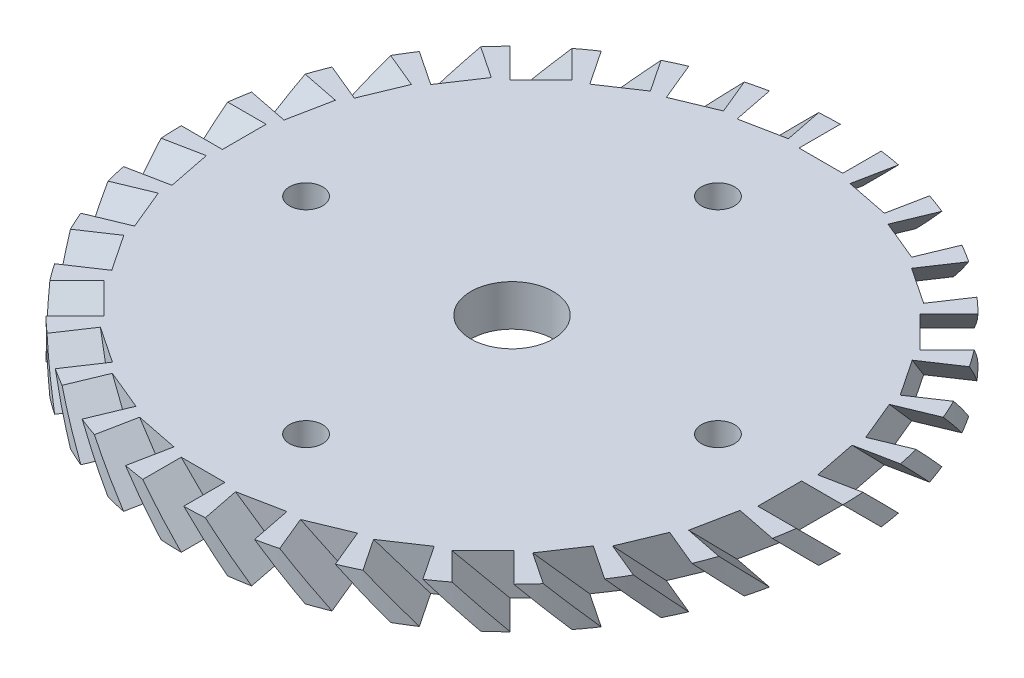
SolidWorks part; units mm, degrees
material "Nickel"
ref_plane "Front Plane" through (0, 0, 0) normal (0, 0, 1) x (1, 0, 0)
ref_plane "Top Plane" through (0, 0, 0) normal (0, 1, 0) x (1, 0, 0)
ref_plane "Right Plane" through (0, 0, 0) normal (1, 0, 0) x (0, 0, -1)
sketch "Sketch1" plane through (0, 0, 0) normal (0, 1, 0) x (1, 0, 0)
  circle A0 centre (0, 0) radius 6.35
  circle A1 centre (0, 0) radius 50.8
  dimension "D1" = 12.7
  dimension "D2" = 101.6
extrude "Boss-Extrude1" add sketch "Sketch1" along normal blind 6.35
ref_plane "Plane1" through (0, 0, 50.8) normal (0, 0, 1) x (1, 0, 0)
sketch "Sketch2" plane through (0, 0, 50.8) normal (0, 0, 1) x (1, 0, 0)
  line L0 (-11.7866, 18.3292) -> (15.1542, -8.6116)
  line L1 (-11.7866, 18.3292) -> (-15.1542, 14.9616)
  line L2 (15.1542, -8.6116) -> (11.7866, -11.9792)
  line L3 (-15.1542, 14.9616) -> (11.7866, -11.9792)
  line L4 (-11.7866, 18.3292) -> (11.7866, -11.9792) construction
  line L5 (15.1542, -8.6116) -> (-15.1542, 14.9616) construction
  line L6 (0, 0) -> (0, 6.35) construction
  line L7 (50.8, 6.35) -> (-50.8, 6.35) construction
  line L8 (-50.8, 0) -> (50.8, 0) construction
  point P1 (0, 3.175)
  point P10 (0, 0)
  dimension "D1" = 45
  dimension "D2" = 38.1
  dimension "D3" = 4.7625
extrude "Cut-Extrude1" cut sketch "Sketch2" against normal blind 6.35
pattern_circular "CirPattern1" count 32 over 360 about axis through (0, 0, 0) along (0, 1, 0) of "Cut-Extrude1"
hole_wizard "CSK for #10 Flat Head Machine Screw (100)1" positions "3DSketch1" profile "Sketch4" countersink size "#10" standard "ANSI Inch" end condition through all
sketch3d "3DSketch1"
  line L2 (0, 0, 31.75) -> (0, 0, 6.35)
  line L4 (0, 0, 6.35) -> (17.4888, 0, 6.35) construction
  circle A0 centre (0, 0, 0) radius 6.35 construction
  point P0 (0, 0, 31.75)
  point P12 (0, 6.35, 0)
  dimension "D1" = 25.4
sketch "Sketch4" plane through (0, 0, 31.75) normal (1, 0, 0) x (0, 0, -1)
  line L0 (0, 0) -> (0, 6.35)
  line L1 (0, 6.35) -> (2.5527, 6.35)
  line L2 (2.5527, 6.35) -> (2.5527, 1.9608)
  line L3 (2.5527, 1.9608) -> (4.8895, 0)
  line L5 (4.8895, 0) -> (0, 0)
  line L6 (-2.5527, 1.9608) -> (-4.8895, 0) construction
  line L11 (0, -6.35) -> (0, 107.95) construction
  dimension "Thru Hole Dia." = 5.1054
  dimension "Thru Hole Depth" = 6.35
  dimension "Near C'Sink Dia." = 9.779
  dimension "Near C'Sink Angle" = 100
pattern_circular "CirPattern2" count 4 over 360 about axis through (0, 0, 0) along (0, 1, 0) of "CSK for #10 Flat Head Machine Screw (100)1"
